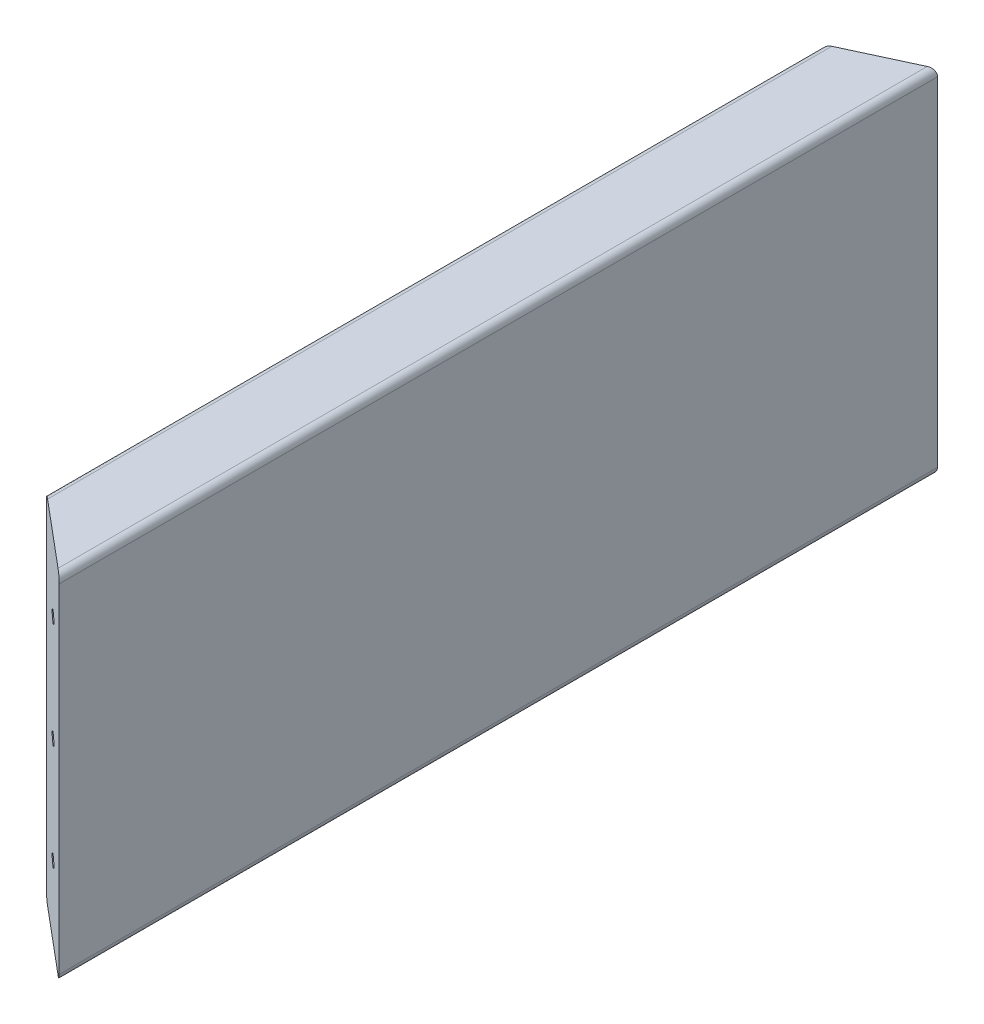
SolidWorks part; units mm, degrees
material "Beech"
ref_plane "Front Plane" through (0, 0, 0) normal (0, 0, 1) x (1, 0, 0)
ref_plane "Top Plane" through (0, 0, 0) normal (0, 1, 0) x (1, 0, 0)
ref_plane "Right Plane" through (0, 0, 0) normal (1, 0, 0) x (0, 0, -1)
sketch "Sketch1" plane through (0, 0, 0) normal (0, 0, 1) x (1, 0, 0)
  line L0 (-31.1883, 134.2727) -> (-31.1883, -65.7273)
  line L1 (-31.1883, -65.7273) -> (13.8117, -65.7273)
  line L2 (-31.1883, 134.2727) -> (13.8117, 134.2727)
  line L3 (13.8117, 134.2727) -> (13.8117, -65.7273)
extrude "Boss-Extrude1" add sketch "Sketch1" along normal blind 510
fillet "Fillet1" radius 4 4 edges at (-31.1883, -65.7273, 255) (13.8117, -65.7273, 255) (-31.1883, 134.2727, 255) (13.8117, 134.2727, 255)
sketch "Sketch2" plane through (0, 134.2727, 0) normal (0, 1, 0) x (1, 0, 0)
  line L0 (13.8117, -498.6746) -> (-31.1883, -460.918)
  line L1 (13.8117, 0) -> (13.8117, -510) construction
  line L2 (-725.4918, 121.6281) -> (576.8242, -971.0627) construction
  line L3 (-31.1883, -510) -> (-31.1883, 0) construction
extrude "Cut-Extrude1" cut sketch "Sketch2" against normal through all and the other way through all
sketch "Sketch3" plane through (0, 134.2727, 0) normal (0, 1, 0) x (1, 0, 0)
  line L0 (-31.1883, -20.8775) -> (13.8117, 0)
  line L1 (-31.1883, -460.918) -> (-31.1883, 0) construction
extrude "Cut-Extrude2" cut sketch "Sketch3" against normal through all and the other way through all
hole_wizard "Ø8.0mm Dowel Slot" [suppressed] positions "Sketch4" profile "Sketch5" size "Ø8.0" standard "ISO"
sketch "Sketch4" plane through (-725.4918, -65.7273, -121.6281) normal (0.6428, 0, -0.7661) x (-0.7661, 0, -0.6428)
  point P0 (-872.5, 150)
  point P2 (-872.5, 100)
  point P4 (-872.5, 50)
  dimension "D4" = 50
  dimension "D5" = 50
sketch "Sketch5" plane through (-57.8563, 84.2727, 439.1757) normal (0, 1, 0) x (-0.766, 0, -0.6428)
  line L0 (0, 0) -> (0, 90)
  line L1 (0, 90) -> (4, 87.5966)
  line L2 (4, 87.5966) -> (4, 0.025)
  line L3 (4, 0.025) -> (4.025, 0)
  line L4 (4.025, 0) -> (0, 0)
  line L5 (-4, 0.025) -> (-4.025, 0) construction
  line L6 (0, 90) -> (-4, 87.5966) construction
  line L7 (0, -6.35) -> (0, 107.95) construction
  dimension "Hole Dia." = 8
  dimension "Hole Depth" = 90
  dimension "Near C'Sink Dia." = 8.05
  dimension "Near C'Sink Angle" = 90
  dimension "Drill Angle" = 118
hole_wizard "Ø8.0mm Dowel Slot1" positions "Sketch6" profile "Sketch7" size "Ø8.0" standard "ISO" slot yes
sketch "Sketch6" plane through (-1225.7468, -65.7273, 575.087) normal (-0.4209, 0, -0.9071) x (-0.9071, 0, 0.4209)
  line L0 (-1316.8593, 196) -> (-1316.8593, 4) construction
  point P0 (-1339.3593, 40)
  point P2 (-1339.3593, 100)
  point P4 (-1339.3593, 160)
  dimension "D1" = 22.5
  dimension "D2" = 22.5
  dimension "D3" = 22.5
sketch "Sketch7" plane through (-10.7779, -25.7273, 11.4082) normal (0, 1, 0) x (-0.9071, 0, 0.4209)
  line L0 (0, 0) -> (0, 25)
  line L1 (0, 25) -> (4, 22.5966)
  line L2 (4, 22.5966) -> (4, 0.025)
  line L3 (4, 0.025) -> (4.025, 0)
  line L4 (4.025, 0) -> (0, 0)
  line L5 (-4, 0.025) -> (-4.025, 0) construction
  line L6 (0, 25) -> (-4, 22.5966) construction
  line L7 (0, -6.35) -> (0, 107.95) construction
  dimension "Hole Dia." = 8
  dimension "Hole Depth" = 25
  dimension "Near C'Sink Dia." = 8.05
  dimension "Near C'Sink Angle" = 90
  dimension "Drill Angle" = 118
hole_wizard "Ø8.0mm Dowel Slot2" [suppressed] positions "Sketch8" profile "Sketch9" size "Ø8.0" standard "ISO"
sketch "Sketch8" plane through (-1260.3963, 134.2727, 591.1625) normal (-0.4209, 0, -0.9071) x (0.9071, 0, -0.4209)
  point P0 (1382.1634, 40)
  point P2 (1382.1634, 100)
  point P4 (1382.1634, 160)
sketch "Sketch9" plane through (-6.5986, 94.2727, 9.4693) normal (0, 1, 0) x (-0.9071, 0, 0.4209)
  line L0 (0, 0) -> (0, 25)
  line L1 (0, 25) -> (4, 22.5966)
  line L2 (4, 22.5966) -> (4, 0.025)
  line L3 (4, 0.025) -> (4.025, 0)
  line L4 (4.025, 0) -> (0, 0)
  line L5 (-4, 0.025) -> (-4.025, 0) construction
  line L6 (0, 25) -> (-4, 22.5966) construction
  line L7 (0, -6.35) -> (0, 107.95) construction
  dimension "Hole Dia." = 8
  dimension "Hole Depth" = 25
  dimension "Near C'Sink Dia." = 8.05
  dimension "Near C'Sink Angle" = 90
  dimension "Drill Angle" = 118
hole_wizard "Ø6.0mm Dowel Slot" positions "Sketch10" profile "Sketch11" size "Ø6.0" standard "ISO" slot yes
sketch "Sketch10" plane through (-1255.7682, -65.7273, 566.4634) normal (0, 0, 1) x (1, 0, 0)
  line L1 (1244.85, 160) -> (1250.85, 160) construction
  point P0 (1247.85, 160)
  point P2 (1247.85, 100)
  point P4 (1247.85, 40)
sketch "Sketch11" plane through (-7.9182, 94.2727, 566.4634) normal (1, 0, 0) x (0, -1, 0)
  line L0 (0, 0) -> (0, 130)
  line L1 (0, 130) -> (3, 128.1974)
  line L2 (3, 128.1974) -> (3, 0.025)
  line L3 (3, 0.025) -> (3.025, 0)
  line L4 (3.025, 0) -> (0, 0)
  line L5 (-3, 0.025) -> (-3.025, 0) construction
  line L6 (0, 130) -> (-3, 128.1974) construction
  line L7 (0, -6.35) -> (0, 107.95) construction
  dimension "Hole Dia." = 6
  dimension "Hole Depth" = 130
  dimension "Near C'Sink Dia." = 6.05
  dimension "Near C'Sink Angle" = 90
  dimension "Drill Angle" = 118
hole_wizard "Ø6.0mm Dowel Slot1" [suppressed] positions "Sketch12" profile "Sketch13" size "Ø6.0" standard "ISO"
sketch "Sketch12" plane through (-1255.7682, 146.2727, 510.3782) normal (0, 1, 0) x (0.6428, 0, -0.7661)
  point P0 (1166.0052, -650.3187)
  point P3 (1086.3394, -717.1719)
  point P7 (1006.6736, -784.0252)
  point P9 (927.0078, -850.8784)
  point P11 (847.4962, -917.6022)
sketch "Sketch13" plane through (-8.119, 146.2727, 35.137) normal (1, 0, 0) x (0, 0, 1)
  line L0 (0, 0) -> (0, 30)
  line L1 (0, 30) -> (3, 28.1974)
  line L2 (3, 28.1974) -> (3, 0.025)
  line L3 (3, 0.025) -> (3.025, 0)
  line L4 (3.025, 0) -> (0, 0)
  line L5 (-3, 0.025) -> (-3.025, 0) construction
  line L6 (0, 30) -> (-3, 28.1974) construction
  line L7 (0, -6.35) -> (0, 107.95) construction
  dimension "Hole Dia." = 6
  dimension "Hole Depth" = 30
  dimension "Near C'Sink Dia." = 6.05
  dimension "Near C'Sink Angle" = 90
  dimension "Drill Angle" = 118
hole_wizard "Ø6.0mm Dowel Slot4" positions "Sketch22" profile "Sketch23" size "Ø6.0" standard "ISO" slot yes
sketch "Sketch22" plane through (-1324.7143, -77.7273, 452.5298) normal (0, -1, 0) x (0.6428, 0, -0.7661)
  point P0 (-341.0052, 740.3187)
  point P3 (-261.3394, 807.1719)
  point P6 (-181.7507, 873.9604)
  point P10 (-102.0078, 940.8784)
  point P13 (-22.4962, 1007.6022)
  point P16 (847.4962, 1007.6022)
  point P19 (927.0078, 940.8784)
  point P23 (1006.7507, 873.9604)
  point P25 (1086.3394, 807.1719)
  point P28 (1166.0052, 740.3187)
sketch "Sketch23" plane through (-976.764, -77.7273, 1189.6098) normal (1, 0, 0) x (0, 0, -1)
  line L0 (0, 0) -> (0, 12)
  line L1 (0, 12) -> (3, 10.1974)
  line L2 (3, 10.1974) -> (3, 0)
  line L3 (3, 0) -> (0, 0)
  line L4 (0, 12) -> (-3, 10.1974) construction
  line L5 (0, -6.35) -> (0, 107.95) construction
  dimension "Hole Dia." = 6
  dimension "Hole Depth" = 12
  dimension "Drill Angle" = 118
hole_wizard "Ø6.0mm Dowel Slot7" positions "Sketch28" profile "Sketch29" size "Ø6.0" standard "ISO"
sketch "Sketch28" plane through (-1255.7682, 146.2727, 510.3782) normal (0, 1, 0) x (0.6428, 0, -0.7661)
  point P0 (22.5608, -1722.5)
  point P3 (120.5996, -1722.5)
  point P7 (217.974, -1722.5)
  point P9 (314.7913, -1722.5)
  point P11 (412.5608, -1722.5)
  point P13 (510.3116, -1722.5)
  point P15 (607.5219, -1722.5)
  point P17 (704.9775, -1722.5)
  point P19 (802.5608, -1722.5)
  point P22 (802.5608, -1458.5)
  point P26 (802.5608, -1546.5)
  point P28 (802.5608, -1634.5)
  point P30 (22.5608, -1546.5)
  point P34 (22.5608, -1458.5)
  point P36 (22.5608, -1634.5)
  point P38 (22.5608, -932.5)
  point P41 (-22.4962, -917.6022)
  point P44 (71.2428, -861.25)
  point P48 (120.5996, -883.75)
  point P52 (169.2328, -861.25)
  point P54 (217.974, -883.75)
  point P56 (268.0506, -861.25)
  point P58 (314.7913, -883.75)
  point P60 (364.7201, -861.25)
  point P62 (414.2928, -883.75)
  point P64 (462.5664, -861.25)
  point P66 (511.551, -883.75)
  point P68 (560.2153, -861.25)
  point P70 (657.9263, -861.25)
  point P72 (609.5282, -883.75)
  point P74 (707.1553, -883.75)
  point P76 (755.5069, -861.25)
  point P78 (802.5608, -932.5)
  point P80 (847.4962, -917.6022)
  point P83 (927.0078, -850.8784)
  point P86 (1006.7507, -783.9604)
  point P90 (1086.3394, -717.1719)
  point P93 (802.5608, -761.25)
  point P96 (802.5608, -664.25)
  point P99 (1166.0052, -650.3187)
  point P102 (1185.001, -609.0604)
  point P105 (1185.001, -511.1051)
  point P109 (1185.001, -409.0604)
  point P112 (1185.001, -309.1708)
  point P114 (1185.001, -209.0363)
  point P116 (1185.001, -109.0604)
  point P119 (1185.001, -9.0604)
  point P122 (1021.9151, 22.5)
  point P125 (1024.5, 67.5)
  point P128 (1133.73, 67.5)
  point P131 (1133.73, 22.5)
  point P134 (913.5, 67.5)
  point P137 (910.7185, 22.5)
  point P141 (802.5, 67.5)
  point P147 (802.5, 22.5)
  point P149 (688.5, 67.5)
  point P152 (688.5, 22.5)
  point P154 (577.5192, 67.5)
  point P156 (577.9151, 22.5)
  point P159 (466.3273, 67.5)
  point P161 (466.3273, 22.5)
  point P163 (355.5, 67.5)
  point P166 (355.9151, 22.5)
  point P169 (244.5, 67.5)
  point P172 (244.5, 22.5)
  point P174 (133.5309, 67.5)
  point P176 (133.5309, 22.5)
  point P178 (22.5608, 67.5)
  point P180 (22.5608, 22.5)
  point P182 (-87.7299, 67.5)
  point P184 (-88.0849, 22.5)
  point P187 (-199.0849, 67.5)
  point P190 (-199.0849, 22.5)
  point P193 (-310.0849, 22.5)
  point P196 (-310.0849, 67.5)
  point P199 (-341.0052, -650.3187)
  point P202 (-261.3394, -717.1719)
  point P205 (-181.7507, -783.9604)
  point P209 (-102.0078, -850.8784)
  point P211 (22.5608, -77.5)
  point P214 (22.5608, -179.25)
  point P217 (22.5608, -275.9132)
  point P219 (22.5608, -373.0681)
  point P221 (22.5608, -469.6127)
  point P223 (22.5608, -567.3178)
  point P225 (22.5608, -664.25)
  point P228 (22.5608, -761.25)
  point P231 (802.5608, 167.5)
  point P234 (1185.001, 190.9134)
  point P236 (1185.001, 90.9396)
  point P239 (1185.001, 290.9396)
  point P242 (1185.001, 390.9396)
  point P245 (1185.001, 491.2681)
  point P247 (1185.001, 590.9396)
  point P250 (1185.001, 699.7184)
  point P253 (1166.0052, 740.3187)
  point P256 (1086.3394, 807.1719)
  point P259 (1006.7507, 873.9604)
  point P263 (927.0078, 940.8784)
  point P266 (847.4962, 1007.6022)
  point P269 (802.5608, 1022.8195)
  point P271 (802.5608, 973.75)
  point P274 (802.5608, 951.25)
  point P277 (755.5069, 973.75)
  point P281 (802.5608, 852.5)
  point P284 (707.1553, 951.25)
  point P288 (657.9263, 973.75)
  point P290 (609.5282, 951.25)
  point P292 (560.2153, 973.75)
  point P294 (511.5608, 951.25)
  point P297 (462.5664, 973.75)
  point P299 (412.5608, 951.25)
  point P301 (364.7108, 973.75)
  point P304 (315.9608, 951.25)
  point P307 (266.9108, 973.75)
  point P310 (218.1608, 951.25)
  point P313 (169.1108, 973.75)
  point P316 (120.3608, 951.25)
  point P319 (71.3108, 973.75)
  point P322 (22.5608, 973.75)
  point P325 (22.5608, 1022.5)
  point P328 (22.5608, 951.25)
  point P331 (-102.0078, 940.8784)
  point P334 (-181.7507, 873.9604)
  point P338 (-22.4962, 1007.6022)
  point P341 (-261.3394, 807.1719)
  point P343 (-341.0052, 740.3187)
  point P346 (-360, 699.5681)
  point P349 (-360, 590.9396)
  point P353 (-360, 491.2681)
  point P355 (-360, 390.9396)
  point P357 (-360, 290.9396)
  point P359 (-360, 190.9134)
  point P361 (-360, 90.9396)
  point P363 (-360, -11.9775)
  point P365 (-360, -77.5)
  point P367 (-360, -179.25)
  point P369 (-360, -275.9132)
  point P371 (-360, -373.0681)
  point P373 (-360, -469.6127)
  point P375 (-360, -609.5213)
  point P378 (22.5608, 1812.5)
  point P381 (71.3108, 1812.5)
  point P383 (120.3608, 1812.5)
  point P385 (169.1108, 1812.5)
  point P387 (218.1608, 1812.5)
  point P389 (266.9108, 1812.5)
  point P391 (315.9608, 1812.5)
  point P393 (364.7108, 1812.5)
  point P395 (412.5608, 1812.5)
  point P397 (462.5664, 1812.5)
  point P399 (511.5608, 1812.5)
  point P401 (577.5192, 1812.5)
  point P403 (657.9263, 1812.5)
  point P405 (755.5069, 1812.5)
  point P407 (22.5, 1724.66)
  point P410 (22.5608, 1636.4608)
  point P412 (802.5608, 1812.5)
  point P415 (802.5, 1724.66)
  point P418 (802.5608, 1636.4608)
  point P420 (802.5608, 1548.5146)
  point P432 (22.5608, 851.2226)
  point P434 (22.5608, 754.3426)
  point P436 (22.5608, 657.4768)
  point P438 (22.5608, 559.5838)
  point P440 (22.5608, 463.0035)
  point P442 (22.5608, 365.956)
  point P444 (22.5608, 269.1268)
  point P446 (22.5608, 167.5)
sketch "Sketch29" plane through (78.2854, 146.2727, 1600.248) normal (1, 0, 0) x (0, 0, 1)
  line L0 (0, 0) -> (0, 30)
  line L1 (0, 30) -> (3, 28.1974)
  line L2 (3, 28.1974) -> (3, 0.025)
  line L3 (3, 0.025) -> (3.025, 0)
  line L4 (3.025, 0) -> (0, 0)
  line L5 (-3, 0.025) -> (-3.025, 0) construction
  line L6 (0, 30) -> (-3, 28.1974) construction
  line L7 (0, -6.35) -> (0, 107.95) construction
  dimension "Hole Dia." = 6
  dimension "Hole Depth" = 30
  dimension "Near C'Sink Dia." = 6.05
  dimension "Near C'Sink Angle" = 90
  dimension "Drill Angle" = 118
hole_wizard "Ø6.0mm Dowel Slot8" positions "Sketch30" profile "Sketch31" size "Ø6.0" standard "ISO"
sketch "Sketch30" plane through (-1324.7143, -77.7273, 452.5298) normal (0, -1, 0) x (0.6428, 0, -0.7661)
  point P0 (22.5608, -1722.5)
  point P3 (120.5996, -1722.5)
  point P7 (217.974, -1722.5)
  point P9 (314.7913, -1722.5)
  point P11 (412.5608, -1722.5)
  point P13 (510.3116, -1722.5)
  point P15 (607.5219, -1722.5)
  point P17 (704.9775, -1722.5)
  point P19 (802.5608, -1722.5)
  point P22 (802.5608, -1458.5)
  point P26 (802.5608, -1546.5)
  point P28 (802.5608, -1634.5)
  point P30 (22.5608, -1546.5)
  point P34 (22.5608, -1458.5)
  point P36 (22.5608, -1634.5)
  point P38 (22.5608, -932.5)
  point P41 (-22.4962, -917.6022)
  point P44 (71.2428, -861.25)
  point P48 (120.5996, -883.75)
  point P52 (169.2328, -861.25)
  point P54 (217.974, -883.75)
  point P56 (268.0506, -861.25)
  point P58 (314.7913, -883.75)
  point P60 (364.7201, -861.25)
  point P62 (414.2928, -883.75)
  point P64 (462.5664, -861.25)
  point P66 (511.551, -883.75)
  point P68 (560.2153, -861.25)
  point P70 (657.9263, -861.25)
  point P72 (609.5282, -883.75)
  point P74 (707.1553, -883.75)
  point P76 (755.5069, -861.25)
  point P78 (802.5608, -932.5)
  point P80 (847.4962, -917.6022)
  point P83 (927.0078, -850.8784)
  point P86 (1006.7507, -783.9604)
  point P90 (1086.3394, -717.1719)
  point P93 (802.5608, -761.25)
  point P96 (802.5608, -664.25)
  point P99 (1166.0052, -650.3187)
  point P102 (1185.001, -609.0604)
  point P105 (1185.001, -511.1051)
  point P109 (1185.001, -409.0604)
  point P112 (1185.001, -309.1708)
  point P114 (1185.001, -209.0363)
  point P116 (1185.001, -109.0604)
  point P119 (1185.001, -9.0604)
  point P122 (1021.9151, 22.5)
  point P125 (1024.5, 67.5)
  point P128 (1133.73, 67.5)
  point P131 (1133.73, 22.5)
  point P134 (913.5, 67.5)
  point P137 (910.7185, 22.5)
  point P141 (802.5, 67.5)
  point P147 (802.5, 22.5)
  point P149 (688.5, 67.5)
  point P152 (688.5, 22.5)
  point P154 (577.5192, 67.5)
  point P156 (577.9151, 22.5)
  point P159 (466.3273, 67.5)
  point P161 (466.3273, 22.5)
  point P163 (355.5, 67.5)
  point P166 (355.9151, 22.5)
  point P169 (244.5, 67.5)
  point P172 (244.5, 22.5)
  point P174 (133.5309, 67.5)
  point P176 (133.5309, 22.5)
  point P178 (22.5608, 67.5)
  point P180 (22.5608, 22.5)
  point P182 (-87.7299, 67.5)
  point P184 (-88.0849, 22.5)
  point P187 (-199.0849, 67.5)
  point P190 (-199.0849, 22.5)
  point P193 (-310.0849, 22.5)
  point P196 (-310.0849, 67.5)
  point P199 (-341.0052, -650.3187)
  point P202 (-261.3394, -717.1719)
  point P205 (-181.7507, -783.9604)
  point P209 (-102.0078, -850.8784)
  point P211 (22.5608, -77.5)
  point P214 (22.5608, -179.25)
  point P217 (22.5608, -275.9132)
  point P219 (22.5608, -373.0681)
  point P221 (22.5608, -469.6127)
  point P223 (22.5608, -567.3178)
  point P225 (22.5608, -664.25)
  point P228 (22.5608, -761.25)
  point P231 (802.5608, 167.5)
  point P234 (1185.001, 190.9134)
  point P236 (1185.001, 90.9396)
  point P239 (1185.001, 290.9396)
  point P242 (1185.001, 390.9396)
  point P245 (1185.001, 491.2681)
  point P247 (1185.001, 590.9396)
  point P250 (1185.001, 699.7184)
  point P253 (1166.0052, 740.3187)
  point P256 (1086.3394, 807.1719)
  point P259 (1006.7507, 873.9604)
  point P263 (927.0078, 940.8784)
  point P266 (847.4962, 1007.6022)
  point P269 (802.5608, 1022.8195)
  point P271 (802.5608, 973.75)
  point P274 (802.5608, 951.25)
  point P277 (755.5069, 973.75)
  point P281 (802.5608, 852.5)
  point P284 (707.1553, 951.25)
  point P288 (657.9263, 973.75)
  point P290 (609.5282, 951.25)
  point P292 (560.2153, 973.75)
  point P294 (511.5608, 951.25)
  point P297 (462.5664, 973.75)
  point P299 (412.5608, 951.25)
  point P301 (364.7108, 973.75)
  point P304 (315.9608, 951.25)
  point P307 (266.9108, 973.75)
  point P310 (218.1608, 951.25)
  point P313 (169.1108, 973.75)
  point P316 (120.3608, 951.25)
  point P319 (71.3108, 973.75)
  point P322 (22.5608, 973.75)
  point P325 (22.5608, 1022.5)
  point P328 (22.5608, 951.25)
  point P331 (-102.0078, 940.8784)
  point P334 (-181.7507, 873.9604)
  point P338 (-22.4962, 1007.6022)
  point P341 (-261.3394, 807.1719)
  point P343 (-341.0052, 740.3187)
  point P346 (-360, 699.5681)
  point P349 (-360, 590.9396)
  point P353 (-360, 491.2681)
  point P355 (-360, 390.9396)
  point P357 (-360, 290.9396)
  point P359 (-360, 190.9134)
  point P361 (-360, 90.9396)
  point P363 (-360, -11.9775)
  point P365 (-360, -77.5)
  point P367 (-360, -179.25)
  point P369 (-360, -275.9132)
  point P371 (-360, -373.0681)
  point P373 (-360, -469.6127)
  point P375 (-360, -609.5213)
  point P378 (22.5608, 1812.5)
  point P381 (71.3108, 1812.5)
  point P383 (120.3608, 1812.5)
  point P385 (169.1108, 1812.5)
  point P387 (218.1608, 1812.5)
  point P389 (266.9108, 1812.5)
  point P391 (315.9608, 1812.5)
  point P393 (364.7108, 1812.5)
  point P395 (412.5608, 1812.5)
  point P397 (462.5664, 1812.5)
  point P399 (511.5608, 1812.5)
  point P401 (577.5192, 1812.5)
  point P403 (657.9263, 1812.5)
  point P405 (755.5069, 1812.5)
  point P407 (22.5, 1724.66)
  point P410 (22.5608, 1636.4608)
  point P412 (802.5608, 1812.5)
  point P415 (802.5, 1724.66)
  point P418 (802.5608, 1636.4608)
  point P420 (802.5608, 1548.5146)
  point P432 (22.5608, 851.2226)
  point P434 (22.5608, 754.3426)
  point P436 (22.5608, 657.4768)
  point P438 (22.5608, 559.5838)
  point P440 (22.5608, 463.0035)
  point P442 (22.5608, 365.956)
  point P444 (22.5608, 269.1268)
  point P446 (22.5608, 167.5)
sketch "Sketch31" plane through (-2629.7657, -77.7273, -671.9061) normal (1, 0, 0) x (0, 0, -1)
  line L0 (0, 0) -> (0, 30)
  line L1 (0, 30) -> (3, 28.1974)
  line L2 (3, 28.1974) -> (3, 0.025)
  line L3 (3, 0.025) -> (3.025, 0)
  line L4 (3.025, 0) -> (0, 0)
  line L5 (-3, 0.025) -> (-3.025, 0) construction
  line L6 (0, 30) -> (-3, 28.1974) construction
  line L7 (0, -6.35) -> (0, 107.95) construction
  dimension "Hole Dia." = 6
  dimension "Hole Depth" = 30
  dimension "Near C'Sink Dia." = 6.05
  dimension "Near C'Sink Angle" = 90
  dimension "Drill Angle" = 118
hole_wizard "Ø6.0mm Dowel Slot9" positions "Sketch32" profile "Sketch33" size "Ø6.0" standard "ISO"
sketch "Sketch32" plane through (-1255.7682, 146.2727, 510.3782) normal (0, 1, 0) x (0.6428, 0, -0.7661)
  point P0 (22.5, 1812.5)
  point P3 (22.5, 1673.4325)
  point P7 (802.5, 1812.5)
  point P10 (802.5, 1673.4325)
  point P14 (802.5, 1569.4538)
  point P16 (802.5608, 973.75)
  point P19 (802.5608, 951.25)
  point P22 (22.5608, 951.25)
  point P25 (22.5608, 973.75)
  point P28 (-22.4962, 1007.6022)
  point P31 (847.4962, 1007.6022)
  point P34 (802.5, 67.5)
  point P38 (802.5, 22.5)
  point P42 (1133.73, 67.5)
  point P45 (1133.73, 22.5)
  point P48 (-310.0849, 67.5)
  point P51 (-310.0849, 22.5)
  point P54 (22.5, 22.5)
  point P56 (22.5, 67.5)
  point P58 (22.5, -861.25)
  point P61 (22.5, -883.75)
  point P64 (802.5, -883.75)
  point P67 (802.5, -861.25)
  point P70 (847.4962, -917.6022)
  point P73 (962.579, -821.028)
  point P77 (-341.0052, -650.3187)
  point P80 (-360, -609.5213)
  point P83 (22.5, -1722.5)
  point P86 (802.5, -1722.5)
  point P89 (22.5, -1466.0091)
  point P91 (802.5, -1466.0091)
  point P93 (-22.4962, -917.6022)
  point P96 (1185.001, 699.7184)
  point P99 (1166.0052, 740.3187)
  point P102 (1185.001, -609.0604)
sketch "Sketch33" plane through (-2629.8047, 146.2727, -671.8596) normal (1, 0, 0) x (0, 0, 1)
  line L0 (0, 0) -> (0, 30)
  line L1 (0, 30) -> (3, 28.1974)
  line L2 (3, 28.1974) -> (3, 0.025)
  line L3 (3, 0.025) -> (3.025, 0)
  line L4 (3.025, 0) -> (0, 0)
  line L5 (-3, 0.025) -> (-3.025, 0) construction
  line L6 (0, 30) -> (-3, 28.1974) construction
  line L7 (0, -6.35) -> (0, 107.95) construction
  dimension "Hole Dia." = 6
  dimension "Hole Depth" = 30
  dimension "Near C'Sink Dia." = 6.05
  dimension "Near C'Sink Angle" = 90
  dimension "Drill Angle" = 118
mirror "Mirror1" [suppressed]
hole_wizard "Ø6.0mm Dowel Slot11" positions "Sketch36" profile "Sketch37"
sketch "Sketch36" plane through (-1255.7682, 146.2727, 510.3782) normal (0, 1, 0) x (0.6428, 0, -0.7661)
  point P0 (22.5, 1812.5)
  point P3 (22.5, 1777.0533)
  point P7 (802.5, 1812.5)
  point P10 (802.5, 1787.0555)
  point P14 (22.5608, 973.75)
  point P17 (22.5608, 951.25)
  point P20 (802.5608, 973.75)
  point P23 (802.5608, 951.25)
  point P26 (22.5, -1455.8975)
  point P28 (802.5, -1462.0727)
  point P30 (802.5, -861.25)
  point P33 (802.5, -883.75)
  point P36 (22.5, -861.25)
  point P39 (22.5, -883.75)
  point P42 (22.5, 67.5)
  point P46 (22.5, 22.5)
  point P50 (802.5, 67.5)
  point P52 (802.5, 22.5)
sketch "Sketch37" plane through (-2629.8047, 146.2727, -671.8596) normal (1, 0, 0) x (0, 0, 1)
  line L0 (0, 0) -> (0, 30)
  line L1 (0, 30) -> (3, 28.1974)
  line L2 (3, 28.1974) -> (3, 0.025)
  line L3 (3, 0.025) -> (3.025, 0)
  line L4 (3.025, 0) -> (0, 0)
  line L5 (-3, 0.025) -> (-3.025, 0) construction
  line L6 (0, 30) -> (-3, 28.1974) construction
  line L7 (0, -6.35) -> (0, 107.95) construction
  dimension "Hole Dia." = 6
  dimension "Hole Depth" = 30
  dimension "Near C'Sink Dia." = 6.05
  dimension "Near C'Sink Angle" = 90
  dimension "Drill Angle" = 118
hole_wizard "Ø6.0mm Dowel Slot12" positions "Sketch38" profile "Sketch39"
sketch "Sketch38" plane through (-1324.7143, -77.7273, 452.5298) normal (0, -1, 0) x (0.6428, 0, -0.7661)
  point P0 (22.5, 1812.5)
  point P3 (22.5, 1777.0533)
  point P7 (802.5, 1812.5)
  point P10 (802.5, 1787.0555)
  point P14 (22.5608, 973.75)
  point P17 (22.5608, 951.25)
  point P20 (802.5608, 973.75)
  point P23 (802.5608, 951.25)
  point P26 (22.5, -1455.8975)
  point P28 (802.5, -1462.0727)
  point P30 (802.5, -861.25)
  point P33 (802.5, -883.75)
  point P36 (22.5, -861.25)
  point P39 (22.5, -883.75)
  point P42 (22.5, 67.5)
  point P46 (22.5, 22.5)
  point P50 (802.5, 67.5)
  point P52 (802.5, 22.5)
sketch "Sketch39" plane through (78.2464, -77.7273, 1600.2945) normal (1, 0, 0) x (0, 0, -1)
  line L0 (0, 0) -> (0, 30)
  line L1 (0, 30) -> (3, 28.1974)
  line L2 (3, 28.1974) -> (3, 0.025)
  line L3 (3, 0.025) -> (3.025, 0)
  line L4 (3.025, 0) -> (0, 0)
  line L5 (-3, 0.025) -> (-3.025, 0) construction
  line L6 (0, 30) -> (-3, 28.1974) construction
  line L7 (0, -6.35) -> (0, 107.95) construction
  dimension "Hole Dia." = 6
  dimension "Hole Depth" = 30
  dimension "Near C'Sink Dia." = 6.05
  dimension "Near C'Sink Angle" = 90
  dimension "Drill Angle" = 118
hole_wizard "Ø6.0mm Dowel Slot14" [suppressed] positions "Sketch42" profile "Sketch43" size "Ø6.0" standard "ISO"
sketch "Sketch42" plane through (-1324.7143, -77.7273, 452.5298) normal (0, -1, 0) x (0.6428, 0, -0.7661)
  point P0 (22.5, 1726.5)
  point P4 (22.5, 1640.5)
  point P6 (802.5, 1726.5)
  point P10 (802.5, 1640.5)
  point P12 (22.5, -1462.5)
  point P14 (22.5, -1636.5)
  point P16 (802.5, -1462.5)
  point P18 (802.5, -1636.5)
  point P19 (22.5, -1722.5)
  point P22 (802.5, -1722.5)
  point P25 (22.5, -1550.5)
  point P27 (802.5, -1550.5)
  point P33 (120, -1722.5)
  point P37 (217.5, -1722.5)
  point P39 (315, -1722.5)
  point P41 (412.5, -1722.5)
  point P43 (510, -1722.5)
  point P45 (607.5, -1722.5)
  point P48 (705, -1722.5)
  point P51 (22.5, -861.25)
  point P54 (22.5, -883.75)
  point P57 (-22.4962, -917.6022)
  point P60 (802.5, -861.25)
  point P63 (802.5, -883.75)
  point P66 (847.4962, -917.6022)
  point P69 (802.5, -964.6721)
  point P71 (22.5, -964.6721)
  point P73 (-341.0052, -650.3187)
  point P76 (1166.0052, -650.3187)
  point P79 (1185.001, -609.0604)
  point P82 (-360, -609.5213)
  point P85 (-310.0849, 22.5)
  point P88 (-310.0849, 67.5)
  point P91 (22.5, 67.5)
  point P95 (22.5, 22.5)
  point P99 (802.5, 67.5)
  point P101 (802.5, 22.5)
  point P103 (1133.73, 67.5)
  point P106 (1133.73, 22.5)
  point P109 (1185.001, 699.7184)
  point P112 (1166.0052, 740.3187)
  point P115 (802.5608, 973.75)
  point P118 (802.5608, 951.25)
  point P121 (847.4962, 1007.6022)
  point P124 (-22.4962, 1007.6022)
  point P127 (22.5608, 973.75)
  point P130 (22.5608, 951.25)
  point P133 (-341.0052, 740.3187)
  point P136 (-360, 699.5681)
  point P139 (22.5, 1812.5)
  point P142 (802.5, 1812.5)
  point P148 (22.5, 1552.5)
  point P150 (802.5, 1552.5)
  point P155 (22.5, 1053.7821)
  point P157 (802.5, 1053.7821)
  point P160 (-102.162, -850.749)
  point P164 (-181.8278, -783.8957)
  point P166 (-261.4937, -717.0425)
  point P168 (927.162, -850.749)
  point P172 (1006.8278, -783.8957)
  point P174 (1086.4937, -717.0425)
  point P176 (1086.4937, 807.0425)
  point P180 (1006.8278, 873.8957)
  point P182 (927.162, 940.749)
  point P184 (-102.162, 940.749)
  point P188 (-181.8278, 873.8957)
  point P190 (-261.4937, 807.0425)
  point P193 (-199.2249, 67.5)
  point P195 (-88.3649, 67.5)
  point P197 (-199.2249, 22.5)
  point P199 (-88.3649, 22.5)
  point P201 (912.01, 67.5)
  point P203 (1022.87, 67.5)
  point P205 (912.01, 22.5)
  point P207 (1022.87, 22.5)
  point P209 (-360, -508.8213)
  point P213 (-360, -408.1213)
  point P217 (-360, -307.4213)
  point P219 (-360, -307.2046)
  point P221 (-360, -206.7213)
  point P223 (-360, -106.0213)
  point P225 (-360, -5.3213)
  point P227 (-360, 95.3787)
  point P229 (-360, 196.0787)
  point P231 (-360, 296.7787)
  point P237 (-360, 397.4787)
  point P239 (-360, 498.1787)
  point P241 (-360, 598.8787)
  point P242 (1185.001, -508.3604)
  point P246 (1185.001, -407.6604)
  point P248 (1185.001, -306.9604)
  point P250 (1185.001, -206.2604)
  point P252 (1185.001, -105.5604)
  point P254 (1185.001, -4.8604)
  point P256 (1185.001, 95.8396)
  point P258 (1185.001, 196.5396)
  point P260 (1185.001, 297.2396)
  point P262 (1185.001, 397.9396)
  point P264 (1185.001, 498.6396)
  point P266 (1185.001, 599.3396)
  point P268 (120, 67.5)
  point P270 (217.5, 67.5)
  point P272 (315, 67.5)
  point P274 (412.5, 67.5)
  point P276 (607.5, 67.5)
  point P278 (705, 67.5)
  point P283 (510, 67.5)
  point P292 (120, 22.5)
  point P294 (217.5, 22.5)
  point P296 (315, 22.5)
  point P300 (510, 22.5)
  point P302 (607.5, 22.5)
  point P304 (705, 22.5)
  point P307 (412.5, 22.5)
  point P309 (22.5, -750.78)
  point P311 (22.5, -640.31)
  point P313 (22.5, -529.84)
  point P315 (22.5, -419.37)
  point P317 (22.5, -308.9)
  point P319 (22.5, -198.43)
  point P321 (22.5, -87.96)
  point P324 (802.5, -750.78)
  point P326 (802.5, -640.31)
  point P328 (802.5, -529.84)
  point P330 (802.5, -419.37)
  point P332 (802.5, -308.9)
  point P334 (802.5, -198.43)
  point P336 (802.5, -87.96)
  point P337 (22.5, 177.97)
  point P339 (22.5, 288.44)
  point P341 (22.5, 398.91)
  point P343 (22.5, 509.38)
  point P345 (22.5, 619.85)
  point P347 (22.5, 730.32)
  point P349 (22.5, 840.79)
  point P352 (802.5, 177.97)
  point P354 (802.5, 288.44)
  point P356 (802.5, 509.38)
  point P358 (802.5, 397.9396)
  point P360 (802.5, 619.85)
  point P362 (802.5, 730.32)
  point P364 (802.5, 840.79)
  point P365 (120, 1812.5)
  point P369 (217.5, 1812.5)
  point P373 (315, 1812.5)
  point P375 (412.5, 1812.5)
  point P377 (510, 1812.5)
  point P379 (607.5, 1812.5)
  point P381 (705, 1812.5)
  point P386 (120.0608, 951.25)
  point P390 (217.5608, 951.25)
  point P392 (315.0608, 951.25)
  point P397 (412.5608, 951.25)
  point P399 (510.0608, 951.25)
  point P401 (607.5608, 951.25)
  point P404 (705.0608, 951.25)
  point P406 (656.3108, 973.75)
  point P410 (558.8108, 973.75)
  point P412 (461.3108, 973.75)
  point P414 (363.8108, 973.75)
  point P421 (266.3108, 973.75)
  point P423 (168.8108, 973.75)
  point P426 (120, -861.25)
  point P430 (217.5, -861.25)
  point P432 (315, -861.25)
  point P434 (412.5, -861.25)
  point P436 (510, -861.25)
  point P438 (607.5, -861.25)
  point P440 (705, -861.25)
  point P446 (656.25, -883.75)
  point P450 (558.75, -883.75)
  point P452 (461.25, -883.75)
  point P454 (168.75, -883.75)
  point P456 (266.25, -883.75)
  point P458 (363.75, -883.75)
sketch "Sketch43" plane through (12.3645, -77.7273, 1545.0172) normal (1, 0, 0) x (0, 0, -1)
  line L0 (0, 0) -> (0, 30)
  line L1 (0, 30) -> (3, 28.1974)
  line L2 (3, 28.1974) -> (3, 0.025)
  line L3 (3, 0.025) -> (3.025, 0)
  line L4 (3.025, 0) -> (0, 0)
  line L5 (-3, 0.025) -> (-3.025, 0) construction
  line L6 (0, 30) -> (-3, 28.1974) construction
  line L7 (0, -6.35) -> (0, 107.95) construction
  dimension "Hole Dia." = 6
  dimension "Hole Depth" = 30
  dimension "Near C'Sink Dia." = 6.05
  dimension "Near C'Sink Angle" = 90
  dimension "Drill Angle" = 118
hole_wizard "Ø6.0mm Dowel Slot15" [suppressed] positions "Sketch44" profile "Sketch45" size "Ø6.0" standard "ISO"
sketch "Sketch44" plane through (-1255.7682, 146.2727, 510.3782) normal (0, 1, 0) x (0.6428, 0, -0.7661)
  point P0 (22.5, 1726.5)
  point P4 (22.5, 1640.5)
  point P6 (802.5, 1726.5)
  point P10 (802.5, 1640.5)
  point P12 (22.5, -955.9606)
  point P14 (22.5, -1636.5)
  point P16 (802.5, -1462.5)
  point P18 (802.5, -1636.5)
  point P19 (22.5, -1722.5)
  point P22 (802.5, -1722.5)
  point P25 (22.5, -1550.5)
  point P27 (802.5, -778.9107)
  point P33 (120, -1722.5)
  point P37 (217.5, -1722.5)
  point P39 (315, -1722.5)
  point P41 (412.5, -1722.5)
  point P43 (510, -1722.5)
  point P45 (607.5, -1722.5)
  point P48 (705, -1722.5)
  point P51 (22.5, -861.25)
  point P54 (22.5, -883.75)
  point P57 (-22.4962, -917.6022)
  point P60 (802.5, -861.25)
  point P63 (802.5, -883.75)
  point P66 (847.4962, -917.6022)
  point P69 (802.5, -536.8366)
  point P71 (22.5, -750.2496)
  point P73 (-341.0052, -650.3187)
  point P76 (1166.0052, -650.3187)
  point P79 (2543.5014, 245.8654)
  point P82 (-501.5002, -524.8138)
  point P85 (-310.0849, -433.3306)
  point P88 (-310.0849, -388.3306)
  point P91 (22.5, -388.3306)
  point P95 (22.5, -433.3306)
  point P99 (802.5, -388.3306)
  point P101 (802.5, -433.3306)
  point P103 (1133.73, -388.3306)
  point P106 (1133.73, -433.3306)
  point P109 (2543.5014, -171.034)
  point P112 (1166.0052, 740.3187)
  point P115 (802.5608, 951.25)
  point P118 (802.5608, 951.25)
  point P121 (847.4962, 1007.6022)
  point P124 (-22.4962, 1007.6022)
  point P127 (22.5608, 951.25)
  point P130 (22.5608, 951.25)
  point P133 (-341.0052, 740.3187)
  point P136 (-501.5002, 393.1551)
  point P139 (22.5, 1812.5)
  point P142 (802.5, 1812.5)
  point P148 (22.5, 1552.5)
  point P150 (802.5, 1552.5)
  point P155 (22.5, 83.8102)
  point P157 (802.5, 297.2232)
  point P160 (-102.162, -850.749)
  point P164 (-181.8278, -783.8957)
  point P166 (-261.4937, -717.0425)
  point P168 (927.162, -850.749)
  point P172 (1006.8278, -783.8957)
  point P174 (1086.4937, -717.0425)
  point P176 (1086.4937, 807.0425)
  point P180 (1006.8278, 873.8957)
  point P182 (927.162, 940.749)
  point P184 (-102.162, 940.749)
  point P188 (-181.8278, 873.8957)
  point P190 (-261.4937, 807.0425)
  point P193 (-199.2249, -388.3306)
  point P195 (-88.3649, -388.3306)
  point P197 (-199.2249, -433.3306)
  point P199 (-88.3649, -433.3306)
  point P201 (912.01, -388.3306)
  point P203 (1022.87, -388.3306)
  point P205 (912.01, -433.3306)
  point P207 (1022.87, -433.3306)
  point P209 (-501.5002, -424.1138)
  point P213 (-501.5002, -323.4138)
  point P217 (-501.5002, -222.7138)
  point P219 (-501.5002, -307.2046)
  point P221 (-501.5002, -122.0138)
  point P223 (-501.5002, -21.3138)
  point P225 (-501.5002, 79.3862)
  point P227 (-501.5002, 180.0862)
  point P229 (-501.5002, 280.7862)
  point P231 (-501.5002, 381.4862)
  point P237 (-501.5002, 482.1862)
  point P239 (-501.5002, 582.8862)
  point P241 (-501.5002, 683.5862)
  point P242 (2543.5014, 145.1654)
  point P246 (2543.5014, 44.4654)
  point P248 (2543.5014, -56.2346)
  point P250 (2543.5014, -156.9346)
  point P252 (2543.5014, -257.6346)
  point P254 (2543.5014, -358.3346)
  point P256 (2543.5014, -459.0346)
  point P258 (2543.5014, -559.7346)
  point P260 (2543.5014, -660.4346)
  point P262 (2543.5014, -761.1346)
  point P264 (2543.5014, -861.8346)
  point P266 (2543.5014, -962.5346)
  point P268 (120, -388.3306)
  point P270 (217.5, -388.3306)
  point P272 (315, -388.3306)
  point P274 (592.3435, -336.1213)
  point P276 (607.5, -388.3306)
  point P278 (705, -388.3306)
  point P283 (510, -388.3306)
  point P292 (120, -433.3306)
  point P294 (217.5, -433.3306)
  point P296 (315, -433.3306)
  point P300 (510, -433.3306)
  point P302 (607.5, -433.3306)
  point P304 (705, -433.3306)
  point P307 (412.5, -433.3306)
  point P309 (22.5, -750.78)
  point P311 (22.5, -640.31)
  point P313 (22.5, -529.84)
  point P315 (22.5, -419.37)
  point P317 (22.5, -308.9)
  point P319 (22.5, -198.43)
  point P321 (22.5, -87.96)
  point P324 (802.5, -750.78)
  point P326 (802.5, -402.8046)
  point P328 (802.5, -357.1566)
  point P330 (802.5, -311.5085)
  point P332 (802.5, -265.8604)
  point P334 (802.5, -220.2123)
  point P336 (802.5, -174.5642)
  point P337 (22.5, -277.8606)
  point P339 (22.5, -167.3906)
  point P341 (22.5, -56.9206)
  point P343 (22.5, 53.5494)
  point P345 (22.5, 164.0194)
  point P347 (22.5, 274.4894)
  point P349 (22.5, 384.9594)
  point P352 (802.5, -64.6773)
  point P354 (802.5, -19.0293)
  point P356 (802.5, 72.2669)
  point P358 (802.5, 26.2178)
  point P360 (802.5, 117.915)
  point P362 (802.5, 228.385)
  point P364 (802.5, 209.2112)
  point P365 (1224.4002, 2039.7886)
  point P369 (1161.3433, 1965.4241)
  point P373 (1089.7554, 1899.2318)
  point P375 (1008.8996, 1844.747)
  point P377 (920.7821, 1803.0151)
  point P379 (823.4819, 1796.7769)
  point P381 (755.0534, 1727.3233)
  point P386 (120.0608, 951.25)
  point P390 (217.5608, 951.25)
  point P392 (315.0608, 951.25)
  point P397 (412.5608, 951.25)
  point P399 (510.0608, 951.25)
  point P401 (607.5608, 951.25)
  point P404 (705.0608, 951.25)
  point P406 (656.3108, 951.25)
  point P410 (558.8108, 951.25)
  point P412 (461.3108, 951.25)
  point P414 (363.8108, 951.25)
  point P421 (266.3108, 951.25)
  point P423 (168.8108, 951.25)
  point P426 (120, -861.25)
  point P430 (217.5, -861.25)
  point P432 (315, -861.25)
  point P434 (412.5, -861.25)
  point P436 (510, -861.25)
  point P438 (607.5, -861.25)
  point P440 (705, -861.25)
  point P446 (656.25, -883.75)
  point P450 (558.75, -883.75)
  point P452 (461.25, -883.75)
  point P454 (168.75, -883.75)
  point P456 (266.25, -883.75)
  point P458 (363.75, -883.75)
sketch "Sketch45" plane through (-2563.9228, 146.2727, -616.5823) normal (1, 0, 0) x (0, 0, 1)
  line L0 (0, 0) -> (0, 30)
  line L1 (0, 30) -> (3, 28.1974)
  line L2 (3, 28.1974) -> (3, 0.025)
  line L3 (3, 0.025) -> (3.025, 0)
  line L4 (3.025, 0) -> (0, 0)
  line L5 (-3, 0.025) -> (-3.025, 0) construction
  line L6 (0, 30) -> (-3, 28.1974) construction
  line L7 (0, -6.35) -> (0, 107.95) construction
  dimension "Hole Dia." = 6
  dimension "Hole Depth" = 30
  dimension "Near C'Sink Dia." = 6.05
  dimension "Near C'Sink Angle" = 90
  dimension "Drill Angle" = 118
hole_wizard "Ø6.0mm Dowel Slot16" [suppressed] positions "Sketch46" profile "Sketch47" size "Ø6.0" standard "ISO"
sketch "Sketch46" plane through (-1324.7143, -77.7273, 452.5298) normal (0, -1, 0) x (0.6428, 0, -0.7661)
  point P0 (22.5, 1726.5)
  point P4 (22.5, 1640.5)
  point P6 (802.5, 1726.5)
  point P10 (802.5, 1640.5)
  point P12 (22.5, -955.9606)
  point P14 (22.5, -1636.5)
  point P16 (802.5, -1462.5)
  point P18 (802.5, -1636.5)
  point P19 (22.5, -1722.5)
  point P22 (802.5, -1722.5)
  point P25 (22.5, -1550.5)
  point P27 (802.5, -778.9107)
  point P33 (120, -1722.5)
  point P37 (217.5, -1722.5)
  point P39 (315, -1722.5)
  point P41 (412.5, -1722.5)
  point P43 (510, -1722.5)
  point P45 (607.5, -1722.5)
  point P48 (705, -1722.5)
  point P51 (22.5, -861.25)
  point P54 (22.5, -883.75)
  point P57 (-22.4962, -917.6022)
  point P60 (802.5, -861.25)
  point P63 (802.5, -883.75)
  point P66 (847.4962, -917.6022)
  point P69 (802.5, -536.8366)
  point P71 (22.5, -750.2496)
  point P73 (-341.0052, -650.3187)
  point P76 (1166.0052, -650.3187)
  point P82 (-501.5002, -524.8138)
  point P85 (-310.0849, -433.3306)
  point P88 (-310.0849, -388.3306)
  point P91 (22.5, -388.3306)
  point P95 (22.5, -433.3306)
  point P99 (802.5, -388.3306)
  point P101 (802.5, -433.3306)
  point P103 (1133.73, -388.3306)
  point P106 (1133.73, -433.3306)
  point P112 (1166.0052, 740.3187)
  point P115 (802.5608, 973.75)
  point P118 (802.5608, 951.25)
  point P121 (847.4962, 1007.6022)
  point P124 (-22.4962, 1007.6022)
  point P127 (22.5608, 951.25)
  point P130 (22.5608, 951.25)
  point P133 (-341.0052, 740.3187)
  point P136 (-501.5002, 393.0196)
  point P139 (22.5, 1812.5)
  point P142 (802.5, 1812.5)
  point P148 (22.5, 1552.5)
  point P150 (802.5, 1552.5)
  point P155 (22.5, 83.8102)
  point P157 (802.5, 297.2232)
  point P160 (-102.162, -850.749)
  point P164 (-181.8278, -783.8957)
  point P166 (-261.4937, -717.0425)
  point P168 (927.162, -850.749)
  point P172 (1006.8278, -783.8957)
  point P174 (1086.4937, -717.0425)
  point P176 (1086.4937, 807.0425)
  point P180 (1006.8278, 873.8957)
  point P182 (927.162, 940.749)
  point P184 (-102.162, 940.749)
  point P188 (-181.8278, 873.8957)
  point P190 (-261.4937, 807.0425)
  point P193 (-199.2249, -388.3306)
  point P195 (-88.3649, -388.3306)
  point P197 (-199.2249, -433.3306)
  point P199 (-88.3649, -433.3306)
  point P201 (912.01, -388.3306)
  point P203 (1022.87, -388.3306)
  point P205 (912.01, -433.3306)
  point P207 (1022.87, -433.3306)
  point P209 (-501.5002, -424.1138)
  point P213 (-501.5002, -323.4138)
  point P217 (-501.5002, -222.7138)
  point P219 (-501.5002, -307.2046)
  point P221 (-501.5002, -122.0138)
  point P223 (-501.5002, -21.3138)
  point P225 (-501.5002, 79.3862)
  point P227 (-501.5002, 180.0862)
  point P229 (-501.5002, 280.7862)
  point P231 (-501.5002, 381.4862)
  point P237 (-501.5002, 482.1862)
  point P239 (-501.5002, 582.8862)
  point P241 (-501.5002, 683.5862)
  point P266 (2543.5014, -962.5346)
  point P268 (120, -388.3306)
  point P270 (217.5, -388.3306)
  point P272 (315, -388.3306)
  point P276 (607.5, -388.3306)
  point P278 (705, -388.3306)
  point P283 (510, -388.3306)
  point P292 (120, -433.3306)
  point P294 (217.5, -433.3306)
  point P296 (315, -433.3306)
  point P300 (510, -433.3306)
  point P302 (607.5, -433.3306)
  point P304 (705, -433.3306)
  point P307 (412.5, -433.3306)
  point P309 (22.5, -750.78)
  point P311 (22.5, -640.31)
  point P313 (22.5, -529.84)
  point P315 (22.5, -419.37)
  point P317 (22.5, -308.9)
  point P319 (22.5, -198.43)
  point P321 (22.5, -87.96)
  point P324 (802.5, -750.78)
  point P326 (802.5, -402.8046)
  point P328 (802.5, -357.1566)
  point P330 (802.5, -311.5085)
  point P332 (802.5, -265.8604)
  point P334 (802.5, -220.2123)
  point P336 (802.5, -174.5642)
  point P337 (22.5, -277.8606)
  point P339 (22.5, -167.3906)
  point P341 (22.5, -56.9206)
  point P343 (22.5, 53.5494)
  point P345 (22.5, 164.0194)
  point P347 (22.5, 274.4894)
  point P349 (22.5, 384.9594)
  point P352 (802.5, -64.6773)
  point P354 (802.5, -19.0293)
  point P356 (802.5, 72.2669)
  point P358 (802.5, 26.2178)
  point P360 (802.5, 117.915)
  point P362 (802.5, 228.385)
  point P364 (802.5, 209.2112)
  point P365 (120.1194, 1812.7578)
  point P369 (217.6065, 1811.1707)
  point P373 (315.0975, 1809.8441)
  point P375 (412.5944, 1809.0701)
  point P377 (510.0612, 1811.6139)
  point P379 (607.5608, 1811.9117)
  point P381 (705.0231, 1814.6216)
  point P386 (120.0608, 951.25)
  point P390 (217.5608, 951.25)
  point P392 (315.0608, 951.25)
  point P397 (412.5608, 951.25)
  point P399 (510.0608, 951.25)
  point P401 (607.5608, 951.25)
  point P404 (705.0608, 951.25)
  point P406 (656.3108, 973.75)
  point P410 (558.8108, 973.75)
  point P412 (461.3108, 973.75)
  point P414 (363.8108, 973.75)
  point P421 (266.3108, 973.75)
  point P423 (168.8108, 973.75)
  point P426 (120, -861.25)
  point P430 (217.5, -861.25)
  point P432 (315, -861.25)
  point P434 (412.5, -861.25)
  point P436 (510, -861.25)
  point P438 (607.5, -861.25)
  point P440 (705, -861.25)
  point P446 (656.25, -883.75)
  point P450 (558.75, -883.75)
  point P452 (461.25, -883.75)
  point P454 (168.75, -883.75)
  point P456 (266.25, -883.75)
  point P458 (363.75, -883.75)
  point P460 (802.5608, -955.9606)
  point P465 (412.5, -388.3306)
sketch "Sketch47" plane through (12.3645, -77.7273, 1545.0172) normal (1, 0, 0) x (0, 0, -1)
  line L0 (0, 0) -> (0, 30)
  line L1 (0, 30) -> (3, 28.1974)
  line L2 (3, 28.1974) -> (3, 0.025)
  line L3 (3, 0.025) -> (3.025, 0)
  line L4 (3.025, 0) -> (0, 0)
  line L5 (-3, 0.025) -> (-3.025, 0) construction
  line L6 (0, 30) -> (-3, 28.1974) construction
  line L7 (0, -6.35) -> (0, 107.95) construction
  dimension "Hole Dia." = 6
  dimension "Hole Depth" = 30
  dimension "Near C'Sink Dia." = 6.05
  dimension "Near C'Sink Angle" = 90
  dimension "Drill Angle" = 118
hole_wizard "Ø6.0mm Dowel Slot17" positions "Sketch48" profile "Sketch49" size "Ø6.0" standard "ISO" slot yes
sketch "Sketch48" plane through (-1324.7143, -77.7273, 452.5298) normal (0, -1, 0) x (0.6428, 0, -0.7661)
  line L17 (802.5, 1812.5) -> (22.5, 1812.5)
  line L18 (-360, 699.4255) -> (-360, -609.5213)
  line L23 (1185.001, 699.4255) -> (1185, -609.5213)
  point P0 (22.5, 1726.5)
  point P4 (22.5, 1640.5)
  point P6 (802.5, 1726.5)
  point P10 (802.5, 1640.5)
  point P12 (22.5, -955.9606)
  point P14 (22.5, -1636.5)
  point P16 (802.5, -1462.5)
  point P18 (802.5, -1636.5)
  point P19 (22.5, -1722.5)
  point P22 (802.5, -1722.5)
  point P25 (22.5, -1550.5)
  point P27 (802.5, -640.31)
  point P33 (120, -1722.5)
  point P37 (217.5, -1722.5)
  point P39 (315, -1722.5)
  point P41 (412.5, -1722.5)
  point P43 (510, -1722.5)
  point P45 (607.5, -1722.5)
  point P48 (705, -1722.5)
  point P51 (22.5, -861.25)
  point P54 (22.5, -883.75)
  point P57 (-22.4962, -917.6022)
  point P60 (802.5, -861.25)
  point P63 (802.5, -883.75)
  point P66 (847.4962, -917.6022)
  point P69 (802.5, -529.84)
  point P71 (22.5, -750.2496)
  point P73 (-341.0052, -650.3187)
  point P76 (1166.0052, -650.3187)
  point P85 (-310.0849, 22.5)
  point P88 (-310.0849, 67.5)
  point P91 (22.5, 67.5)
  point P95 (22.5, 22.5)
  point P99 (802.5, 67.5)
  point P101 (802.5, 22.5)
  point P103 (1133.73, 67.5)
  point P106 (1133.73, 22.5)
  point P112 (1166.0052, 740.3187)
  point P115 (802.5608, 973.75)
  point P118 (802.5608, 951.25)
  point P121 (847.4962, 1007.6022)
  point P124 (-22.4962, 1007.6022)
  point P127 (22.5608, 951.25)
  point P130 (22.5608, 951.25)
  point P133 (-341.0052, 740.3187)
  point P139 (22.5, 1812.5)
  point P142 (802.5, 1812.5)
  point P148 (22.5, 1552.5)
  point P150 (802.5, 1552.5)
  point P160 (-102.162, -850.749)
  point P164 (-181.8278, -783.8957)
  point P166 (-261.4937, -717.0425)
  point P168 (927.162, -850.749)
  point P172 (1006.8278, -783.8957)
  point P174 (1086.4937, -717.0425)
  point P176 (1086.4937, 807.0425)
  point P180 (1006.8278, 873.8957)
  point P182 (927.162, 940.749)
  point P184 (-102.162, 940.749)
  point P188 (-181.8278, 873.8957)
  point P190 (-261.4937, 807.0425)
  point P193 (-199.2249, 67.5)
  point P195 (-88.3649, 67.5)
  point P197 (-199.2249, 22.5)
  point P199 (-88.3649, 22.5)
  point P201 (912.01, 67.5)
  point P203 (1022.87, 67.5)
  point P205 (912.01, 22.5)
  point P207 (1022.87, 22.5)
  point P268 (120, 67.5)
  point P270 (217.5, 67.5)
  point P272 (315, 67.5)
  point P276 (607.5, 67.5)
  point P278 (705, 67.5)
  point P283 (510, 67.5)
  point P292 (120, 22.5)
  point P294 (217.5, 22.5)
  point P296 (315, 22.5)
  point P300 (510, 22.5)
  point P302 (607.5, 22.5)
  point P304 (705, 22.5)
  point P307 (412.5, 22.5)
  point P309 (22.5, -750.78)
  point P311 (22.5, -640.31)
  point P313 (22.5, -529.84)
  point P315 (22.5, -419.37)
  point P317 (22.5, -308.9)
  point P319 (22.5, -198.43)
  point P321 (22.5, -87.96)
  point P324 (802.5, -750.78)
  point P326 (802.5, -419.37)
  point P330 (802.5, -308.9)
  point P336 (802.5, -198.43)
  point P337 (22.5, 177.97)
  point P339 (22.5, 288.44)
  point P341 (22.5, 398.91)
  point P343 (22.5, 509.38)
  point P345 (22.5, 619.85)
  point P347 (22.5, 730.32)
  point P349 (22.5, 840.79)
  point P352 (802.5, -87.96)
  point P360 (802.5, 177.97)
  point P362 (802.5, 288.44)
  point P365 (120.0003, 1812.7537)
  point P369 (217.5, 1812.5)
  point P373 (315, 1812.5)
  point P375 (412.5, 1812.5)
  point P377 (510, 1812.5)
  point P379 (607.5, 1812.5)
  point P381 (705, 1812.5)
  point P386 (120.0608, 951.25)
  point P390 (217.5608, 951.25)
  point P392 (315.0608, 951.25)
  point P397 (412.5608, 951.25)
  point P399 (510.0608, 951.25)
  point P401 (607.5608, 951.25)
  point P404 (705.0608, 951.25)
  point P406 (656.3108, 973.75)
  point P410 (558.8108, 973.75)
  point P412 (461.3108, 973.75)
  point P414 (363.8108, 973.75)
  point P421 (266.3108, 973.75)
  point P423 (168.8108, 973.75)
  point P426 (120, -861.25)
  point P430 (217.5, -861.25)
  point P432 (315, -861.25)
  point P434 (412.5, -861.25)
  point P436 (510, -861.25)
  point P438 (607.5, -861.25)
  point P440 (705, -861.25)
  point P446 (656.25, -883.75)
  point P450 (558.75, -883.75)
  point P452 (461.25, -883.75)
  point P454 (168.75, -883.75)
  point P456 (266.25, -883.75)
  point P458 (363.75, -883.75)
  point P460 (802.5608, -955.9606)
  point P465 (412.5, 67.5)
  point P509 (802.5, 730.32)
  point P511 (802.5608, 840.79)
  point P517 (802.5, 398.91)
  point P523 (802.5, 509.38)
  point P525 (802.5, 619.85)
  point P528 (-360, 699.4255)
  point P529 (-360, -609.5213)
  point P549 (-360, 598.7255)
  point P551 (-360, 498.0255)
  point P555 (-360, 397.3255)
  point P557 (-360, 296.6255)
  point P559 (-360, 195.9255)
  point P561 (-360, 95.2255)
  point P563 (-360, -5.4745)
  point P568 (-360, -106.1745)
  point P570 (-360, -206.8745)
  point P572 (-360, -307.5745)
  point P574 (-360, -408.2745)
  point P576 (-360, -508.9745)
  point P586 (1185.001, 699.4255)
  point P596 (1185.0009, 598.7255)
  point P598 (1185.0009, 498.0255)
  point P605 (1185.0007, 296.6255)
  point P607 (1185.0006, 195.9255)
  point P609 (1185.0006, 95.2255)
  point P611 (1185.0005, -5.4745)
  point P613 (1185.0004, -106.1745)
  point P615 (1185.0003, -206.8745)
  point P617 (1185.0002, -408.2745)
  point P619 (1185.0001, -508.9745)
  point P622 (1185.0008, 397.3255)
  point P625 (22.5608, 1016.3858)
  point P627 (802.5608, 1016.3858)
  point P628 (802.5608, -1550.5)
  point P630 (22.5608, 973.75)
  point P633 (802.5608, -363.9667)
sketch "Sketch49" plane through (12.3645, -77.7273, 1545.0172) normal (1, 0, 0) x (0, 0, -1)
  line L0 (0, 0) -> (0, 30)
  line L1 (0, 30) -> (3, 28.1974)
  line L2 (3, 28.1974) -> (3, 0.025)
  line L3 (3, 0.025) -> (3.025, 0)
  line L4 (3.025, 0) -> (0, 0)
  line L5 (-3, 0.025) -> (-3.025, 0) construction
  line L6 (0, 30) -> (-3, 28.1974) construction
  line L7 (0, -6.35) -> (0, 107.95) construction
  dimension "Hole Dia." = 6
  dimension "Hole Depth" = 30
  dimension "Near C'Sink Dia." = 6.05
  dimension "Near C'Sink Angle" = 90
  dimension "Drill Angle" = 118
mirror "Mirror3" [suppressed]
